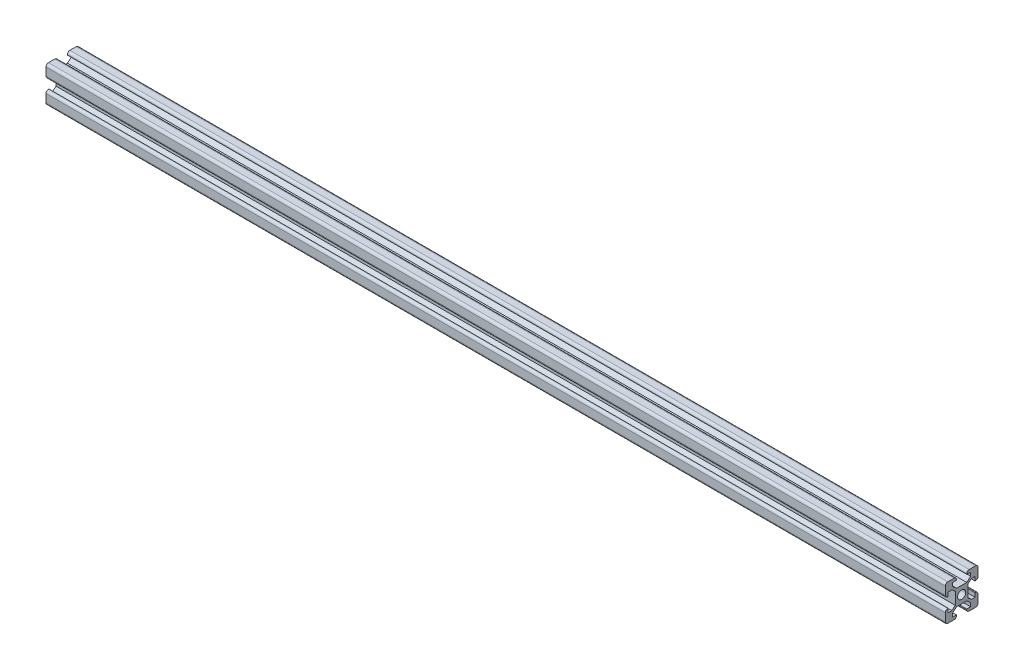
SolidWorks part; units mm, degrees
ref_plane "Front Plane" through (0, 0, 0) normal (0, 0, 1) x (1, 0, 0)
ref_plane "Top Plane" through (0, 0, 0) normal (0, 1, 0) x (1, 0, 0)
ref_plane "Right Plane" through (0, 0, 0) normal (1, 0, 0) x (0, 0, -1)
sketch "Sketch1" plane through (0, 0, 0) normal (1, 0, 0) x (0, 0, -1)
  line L2 (-3.1, 4.9) -> (-5.5, 6.9541)
  line L3 (-5.5, 6.9541) -> (-5.5, 9.2)
  line L4 (-5.5, 9.2) -> (-3.1, 9.2)
  line L5 (-3.1, 9.2) -> (-3.1, 9.5)
  line L7 (-4.6, 11) -> (-8.5, 11)
  line L8 (-10, 9.5) -> (-10, 4.6)
  line L9 (-8.5, 3.1) -> (-8.2, 3.1)
  line L10 (-8.2, 3.1) -> (-8.2, 5.5)
  line L11 (-8.2, 5.5) -> (-5.9541, 5.5)
  line L12 (-5.9541, 5.5) -> (-3.9, 3.7419)
  line L24 (0, 0) -> (0, 16.7357) construction
  line L39 (-3.9, -3.7419) -> (-3.9, 3.7419)
  line L51 (-3.1, 4.9) -> (3.1, 4.9)
  line L53 (0, 4.9) -> (0, -7.4907) construction
  line L54 (-2.5, 0) -> (26.0547, 0) construction
  line L55 (5.9541, 5.5) -> (3.9, 3.7419)
  line L56 (8.2, 5.5) -> (5.9541, 5.5)
  line L57 (8.2, 3.1) -> (8.2, 5.5)
  line L58 (8.5, 3.1) -> (8.2, 3.1)
  line L59 (10, 9.5) -> (10, 4.6)
  line L60 (4.6, 11) -> (8.5, 11)
  line L61 (3.1, 9.2) -> (3.1, 9.5)
  line L62 (5.5, 9.2) -> (3.1, 9.2)
  line L63 (5.5, 6.9541) -> (5.5, 9.2)
  line L64 (3.1, 4.9) -> (5.5, 6.9541)
  line L65 (3.1, -4.9) -> (5.5, -6.9541)
  line L66 (5.5, -6.9541) -> (5.5, -9.2)
  line L67 (5.5, -9.2) -> (3.1, -9.2)
  line L68 (4.6, -11) -> (8.5, -11)
  line L69 (10, -9.5) -> (10, -4.6)
  line L70 (8.5, -3.1) -> (8.2, -3.1)
  line L71 (8.2, -3.1) -> (8.2, -5.5)
  line L72 (8.2, -5.5) -> (5.9541, -5.5)
  line L73 (5.9541, -5.5) -> (3.9, -3.7419)
  line L74 (3.1, -9.5) -> (3.1, -9.2)
  line L75 (-3.1, -9.5) -> (-3.1, -9.2)
  line L76 (-5.9541, -5.5) -> (-3.9, -3.7419)
  line L77 (-8.2, -5.5) -> (-5.9541, -5.5)
  line L78 (-8.2, -3.1) -> (-8.2, -5.5)
  line L79 (-8.5, -3.1) -> (-8.2, -3.1)
  line L80 (-10, -9.5) -> (-10, -4.6)
  line L81 (-4.6, -11) -> (-8.5, -11)
  line L82 (-5.5, -9.2) -> (-3.1, -9.2)
  line L83 (-5.5, -6.9541) -> (-5.5, -9.2)
  line L84 (-3.1, -4.9) -> (-5.5, -6.9541)
  line L85 (-3.1, -4.9) -> (3.1, -4.9)
  line L86 (3.9, 3.7419) -> (3.9, -3.7419)
  circle A0 centre (0, 0) radius 2.5
  arc A6 (-8.5, 11) -> (-10, 9.5) centre (-8.5, 9.5) ccw
  arc A8 (-3.1, 9.5) -> (-4.6, 11) centre (-4.6, 9.5) ccw
  arc A10 (-10, 4.6) -> (-8.5, 3.1) centre (-8.5, 4.6) ccw
  arc A11 (10, 4.6) -> (8.5, 3.1) centre (8.5, 4.6) cw
  arc A12 (3.1, 9.5) -> (4.6, 11) centre (4.6, 9.5) cw
  arc A13 (8.5, 11) -> (10, 9.5) centre (8.5, 9.5) cw
  arc A14 (8.5, -11) -> (10, -9.5) centre (8.5, -9.5) ccw
  arc A15 (3.1, -9.5) -> (4.6, -11) centre (4.6, -9.5) ccw
  arc A16 (10, -4.6) -> (8.5, -3.1) centre (8.5, -4.6) ccw
  arc A17 (-10, -4.6) -> (-8.5, -3.1) centre (-8.5, -4.6) cw
  arc A18 (-3.1, -9.5) -> (-4.6, -11) centre (-4.6, -9.5) cw
  arc A19 (-8.5, -11) -> (-10, -9.5) centre (-8.5, -9.5) cw
  point P49 (3.1, 11)
  point P108 (-3.1, 11)
  dimension "D11" = 2.4
  dimension "D7" = 3.1
  dimension "D5" = 6.1
  dimension "D6" = 6.1
  dimension "D9" = 1.5
  dimension "D12" = 5
  dimension "D13" = 1.5
  dimension "D1" = 1.4
  dimension "D2" = 1.8
  dimension "D3" = 7.9
  dimension "D4" = 6.9
  dimension "D8" = 3.1
  dimension "D10" = 4.5
  dimension "D17" = 1.8
extrude "Boss-Extrude1" add sketch "Sketch1" along normal blind 550
